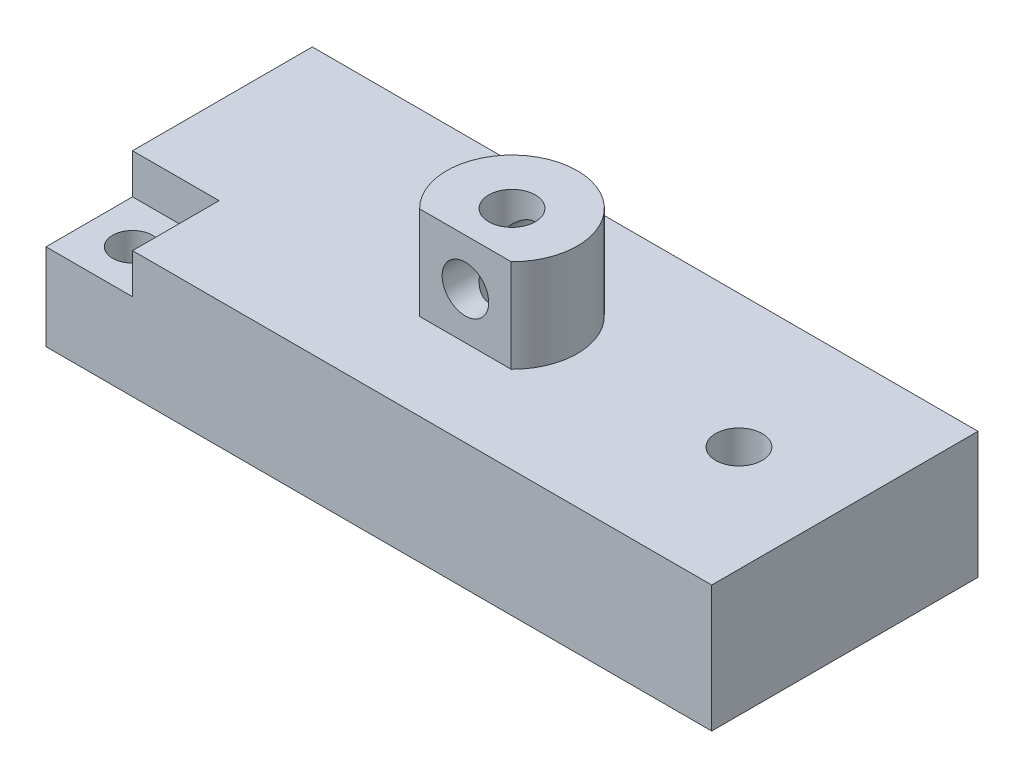
SolidWorks part; units mm, degrees
ref_plane "Спереди" through (0, 0, 0) normal (0, 0, 1) x (1, 0, 0)
ref_plane "Сверху" through (0, 0, 0) normal (0, 1, 0) x (1, 0, 0)
ref_plane "Справа" through (0, 0, 0) normal (1, 0, 0) x (0, 0, -1)
sketch "Эскиз1" plane through (0, 0, 0) normal (0, 1, 0) x (1, 0, 0)
  line L1 (0, 0) -> (-100, 0)
  line L2 (0, 0) -> (0, 40)
  line L3 (0, 40) -> (-100, 40)
  line L4 (-100, 0) -> (-100, 40)
  dimension "D1" = 100
  dimension "D2" = 40
extrude "Бобышка-Вытянуть1" add sketch "Эскиз1" along normal blind 19
sketch "Эскиз2" plane through (0, 19, 0) normal (0, 1, 0) x (1, 0, 0)
  line L0 (-100, 20) -> (0, 20) construction
  line L1 (-100, 40) -> (-100, 0) construction
  line L2 (0, 0) -> (0, 40) construction
  line L3 (-50, 40) -> (-50, 0) construction
  line L4 (0, 40) -> (-100, 40) construction
  line L5 (-100, 0) -> (0, 0) construction
  circle A0 centre (-50, 20) radius 9.8111
extrude "Бобышка-Вытянуть2" add sketch "Эскиз2" along normal blind 14
sketch "Эскиз3" plane through (0, 19, 0) normal (0, 1, 0) x (1, 0, 0)
  line L0 (-100, 40) -> (-100, 0) construction
  line L1 (-100, 13) -> (-87, 13)
  line L2 (-100, 13) -> (-100, 0)
  line L3 (-100, 0) -> (-87, 0)
  line L4 (-87, 13) -> (-87, 0)
  line L5 (-100, 0) -> (0, 0) construction
  dimension "D1" = 13
  dimension "D2" = 13
extrude "Вырез-Вытянуть1" cut sketch "Эскиз3" against normal blind 6
sketch "Эскиз4" plane through (0, 13, 0) normal (0, 1, 0) x (1, 0, 0)
  line L0 (-93.5, 13) -> (-93.5, 0) construction
  line L1 (-87, 13) -> (-100, 13) construction
  line L2 (-100, 0) -> (-87, 0) construction
  line L3 (-100, 6.5) -> (-87, 6.5) construction
  line L4 (-100, 13) -> (-100, 0) construction
  line L5 (-87, 0) -> (-87, 13) construction
  circle A0 centre (-93.5, 6.5) radius 3
  dimension "D1" = 6
extrude "Вырез-Вытянуть2" cut sketch "Эскиз4" against normal through all
sketch "Эскиз5" plane through (0, 33, 0) normal (0, 1, 0) x (1, 0, 0)
  line L0 (-50, 29.8111) -> (-50, 10.1889) construction
  line L1 (-59.8111, 20) -> (-40.1889, 20) construction
  circle A0 centre (-50, 20) radius 9.8111 construction
  circle A1 centre (-50, 20) radius 3.5
  dimension "D1" = 7
extrude "Вырез-Вытянуть3" cut sketch "Эскиз5" against normal through all
sketch "Эскиз6" plane through (0, 19, 0) normal (0, 1, 0) x (1, 0, 0)
  line L0 (-15.9109, 40) -> (-15.9109, 0) construction
  line L1 (0, 40) -> (-100, 40) construction
  line L2 (-87, 0) -> (0, 0) construction
  line L3 (0, 20) -> (-100, 20) construction
  line L4 (0, 0) -> (0, 40) construction
  line L5 (-100, 40) -> (-100, 13) construction
  circle A0 centre (-15.9109, 20) radius 3.5
  dimension "D1" = 7
extrude "Вырез-Вытянуть4" cut sketch "Эскиз6" against normal through all
sketch "Эскиз7" plane through (0, 19, 0) normal (0, 1, 0) x (1, 0, 0)
  line L1 (-87, 13) -> (0, 13)
  line L2 (-87, 13) -> (-87, 0)
  line L3 (-87, 0) -> (0, 0)
  line L4 (0, 13) -> (0, 0)
extrude "Вырез-Вытянуть6" cut sketch "Эскиз7" along normal blind 31
sketch "Эскиз8" plane through (0, 0, -13) normal (0, 0, 1) x (1, 0, 0)
  line L0 (-50, 33) -> (-50, 19) construction
  line L1 (-56.8745, 33) -> (-43.1255, 33) construction
  line L2 (-43.1255, 19) -> (-56.8745, 19) construction
  line L3 (-56.8745, 26) -> (-43.1255, 26) construction
  line L4 (-56.8745, 33) -> (-56.8745, 19) construction
  line L5 (-43.1255, 19) -> (-43.1255, 33) construction
  circle A0 centre (-50, 26) radius 3.5
  dimension "D1" = 7
extrude "Вырез-Вытянуть7" cut sketch "Эскиз8" against normal through all
